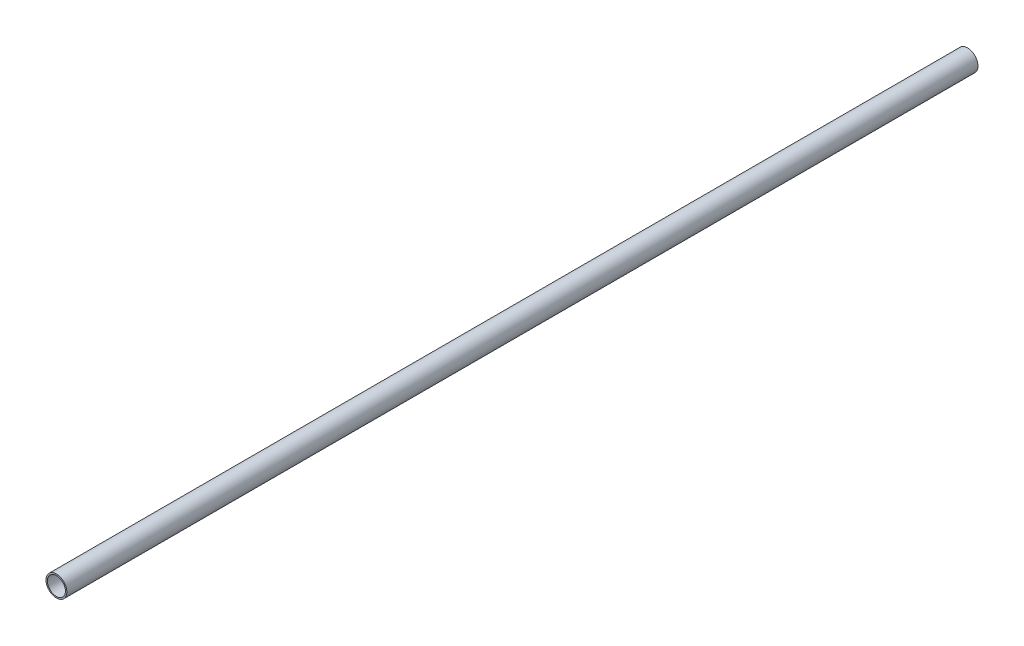
SolidWorks part; units mm, degrees
ref_plane "Front Plane" through (0, 0, 0) normal (0, 0, 1) x (1, 0, 0)
ref_plane "Top Plane" through (0, 0, 0) normal (0, 1, 0) x (1, 0, 0)
ref_plane "Right Plane" through (0, 0, 0) normal (1, 0, 0) x (0, 0, -1)
sketch "Sketch1" plane through (0, 0, 0) normal (0, 0, 1) x (1, 0, 0)
  circle A0 centre (0, 0) radius 15
  circle A1 centre (0, 0) radius 13
  dimension "D1" = 2
  dimension "D2" = 30
extrude "Boss-Extrude1" add sketch "Sketch1" along normal blind 1310
